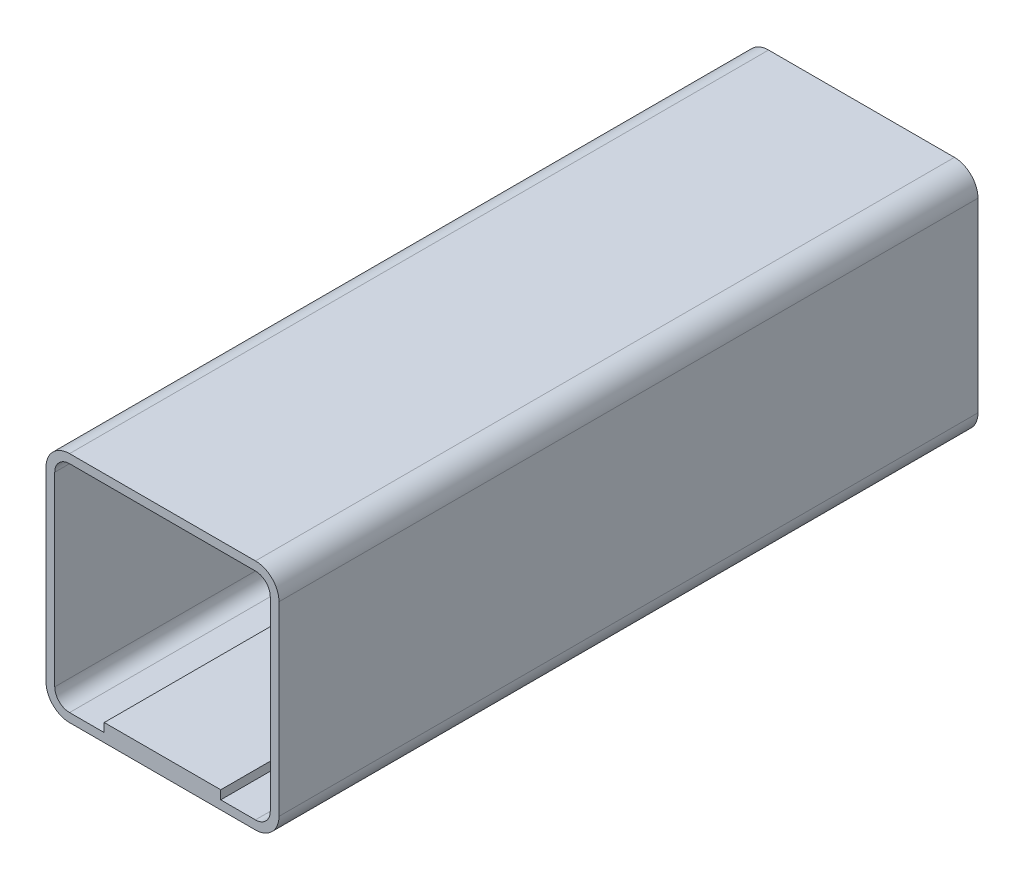
SolidWorks part; units mm, degrees
material "Polyurethane Foam Rigid"
ref_plane "Front Plane" through (0, 0, 0) normal (0, 0, 1) x (1, 0, 0)
ref_plane "Top Plane" through (0, 0, 0) normal (0, 1, 0) x (1, 0, 0)
ref_plane "Right Plane" through (0, 0, 0) normal (1, 0, 0) x (0, 0, -1)
sketch "Sketch1" plane through (0, 0, 0) normal (0, 0, 1) x (1, 0, 0)
  line L0 (-59.737, 59.737) -> (59.737, -59.737) construction
  line L1 (-50.6524, 63.5) -> (50.6524, 63.5)
  line L2 (-63.5, 50.6524) -> (-63.5, -50.6524)
  line L3 (-50.6524, -63.5) -> (50.6524, -63.5)
  line L4 (63.5, 50.6524) -> (63.5, -50.6524)
  arc A0 (63.5, 50.6524) -> (50.6524, 63.5) centre (50.6524, 50.6524) ccw
  arc A1 (50.6524, -63.5) -> (63.5, -50.6524) centre (50.6524, -50.6524) ccw
  arc A2 (-50.6524, -63.5) -> (-63.5, -50.6524) centre (-50.6524, -50.6524) cw
  arc A3 (-63.5, 50.6524) -> (-50.6524, 63.5) centre (-50.6524, 50.6524) cw
  point P0 (0, 0)
  point P1 (0, 0)
  point P18 (59.737, -59.737)
  dimension "D2" = 12.8476
  dimension "D3" = 12.8476
  dimension "D1" = 127
  dimension "D4" = 127
extrude "Boss-Extrude1" add sketch "Sketch1" against normal blind 381 contours L1 A0 L4 A1 L3 A2 L2 A3
shell "Shell1" thickness 4.7625
sketch "Sketch3" plane through (0, 0, 0) normal (0, 0, 1) x (1, 0, 0)
  line L0 (-31.75, -58.7375) -> (31.75, -58.7375)
  line L1 (-50.6524, -58.7375) -> (50.6524, -58.7375) construction
  line L2 (0, -58.7375) -> (0, 0) construction
  line L3 (-31.75, -58.7375) -> (-31.75, -53.975)
  line L4 (-31.75, -53.975) -> (31.75, -53.975)
  line L5 (31.75, -53.975) -> (31.75, -58.7375)
  point P5 (0, -58.7375)
  dimension "D1" = 63.5
  dimension "D2" = 4.7625
extrude "Boss-Extrude2" add sketch "Sketch3" against normal up to surface (381 mm away) up to face at (0, 0, -381)
equation "\"span\"= 48"
equation "\"wing_chord\"= 9"
equation "\"fuse_len\"= 15"
equation "\"fuse_height\"= 5"
equation "\"fuse_wid\"= 5"
equation "\"D1@Boss-Extrude1\"= \"fuse_len\""
equation "\"D1@Sketch1\"= \"fuse_height\""
equation "\"D4@Sketch1\"= \"fuse_wid\""
equation "\"D1@Sketch3\"=\"fuse_wid\"/2"
equation "\"D2@Sketch3\"=3/16"
equation "\"foam_t\"= 0.1875"
equation "\"fuse_inner_arc_length\"= 0.5"
equation "\"fuse_inner_r\"= \"fuse_inner_arc_length\" * 4 / (2*pi)"
equation "\"fuse_outer_r\"= \"fuse_inner_r\" + \"foam_t\""
equation "\"main_spar_len\"= 36"
equation "\"x_fuse_to_wing\"= 3"
equation "\"x_cg_from_le\"= 2.25"
equation "\"boom_len\"= 30"
equation "\"wing_angle\"= 1.5"
equation "\"boom_d\"= 0.75"
equation "\"wing_spar_d\"= 0.375"
equation "\"wing_spar_l\"= 48"
equation "\"wing_spar_spacing\"= 1.35"
equation "\"wing_mount_l\"= 2.5"
equation "\"wing_mount_bolt_spacing\"= \"wing_mount_l\" + 0.5"
equation "\"boom_mount_l\"= 1"
equation "\"vstab_span\"= 6.5"
equation "\"hstab_span\"= 15.25"
equation "\"tail_chord\"= 5"
equation "\"D2@Sketch1\"= \"fuse_outer_r\""
equation "\"D3@Sketch1\"= \"fuse_outer_r\""
equation "\"fuse_inner_h\"= \"fuse_height\" - 2*\"foam_t\""
equation "\"fuse_inner_w\"= \"fuse_wid\" - 2*\"fuse_outer_r\""
